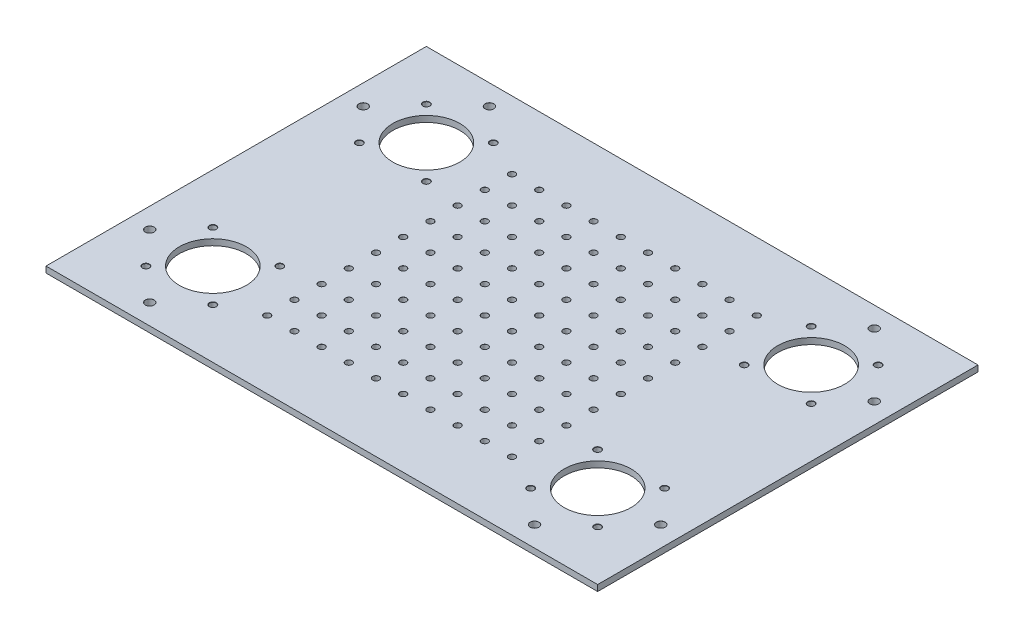
SolidWorks part; units mm, degrees
ref_plane "Front Plane" through (0, 0, 0) normal (0, 0, 1) x (1, 0, 0)
ref_plane "Top Plane" through (0, 0, 0) normal (0, 1, 0) x (1, 0, 0)
ref_plane "Right Plane" through (0, 0, 0) normal (1, 0, 0) x (0, 0, -1)
sketch "Sketch1" plane through (0, 0, 0) normal (0, 1, 0) x (1, 0, 0)
  line L0 (-115.9, 93.7) -> (-115.9, -93.7) construction
  line L1 (-135.9, -93.7) -> (135.9, -93.7)
  line L2 (-135.9, -93.7) -> (-135.9, 93.7)
  line L3 (-135.9, 93.7) -> (135.9, 93.7)
  line L4 (135.9, -93.7) -> (135.9, 93.7)
  line L5 (-135.9, -93.7) -> (135.9, 93.7) construction
  line L6 (-135.9, 93.7) -> (135.9, -93.7) construction
  line L7 (-94.8, -52.6) -> (94.8, -52.6) construction
  line L8 (-94.8, -52.6) -> (-94.8, 52.6) construction
  line L9 (-94.8, 52.6) -> (94.8, 52.6) construction
  line L10 (94.8, -52.6) -> (94.8, 52.6) construction
  line L11 (-94.8, -52.6) -> (94.8, 52.6) construction
  line L12 (-94.8, 52.6) -> (94.8, -52.6) construction
  line L13 (-115.9, 73.7) -> (-73.7, 73.7) construction
  line L14 (-115.9, 73.7) -> (-115.9, 31.5) construction
  line L15 (-115.9, 31.5) -> (-73.7, 31.5) construction
  line L16 (-73.7, 73.7) -> (-73.7, 31.5) construction
  line L17 (-115.9, 73.7) -> (-73.7, 31.5) construction
  line L18 (-115.9, 31.5) -> (-73.7, 73.7) construction
  line L19 (-115.9, 73.7) -> (135.9, 73.7) construction
  line L20 (-135.9, 73.7) -> (-115.9, 73.7) construction
  line L21 (-94.8, 73.7) -> (-94.8, 93.7) construction
  line L22 (-115.9, 52.6) -> (-135.9, 52.6) construction
  line L23 (-60.3, 93.7) -> (-60.3, -93.7) construction
  line L24 (-115.9, -73.7) -> (-73.7, -73.7) construction
  line L25 (-115.9, -73.7) -> (-115.9, -31.5) construction
  line L26 (-115.9, -31.5) -> (-73.7, -31.5) construction
  line L27 (-73.7, -73.7) -> (-73.7, -31.5) construction
  line L28 (-115.9, -73.7) -> (-73.7, -31.5) construction
  line L29 (-115.9, -31.5) -> (-73.7, -73.7) construction
  line L30 (73.7, 73.7) -> (115.9, 73.7) construction
  line L31 (73.7, 73.7) -> (73.7, 31.5) construction
  line L32 (73.7, 31.5) -> (115.9, 31.5) construction
  line L33 (115.9, 73.7) -> (115.9, 31.5) construction
  line L34 (73.7, 73.7) -> (115.9, 31.5) construction
  line L35 (73.7, 31.5) -> (115.9, 73.7) construction
  line L36 (73.7, -31.5) -> (115.9, -31.5) construction
  line L37 (73.7, -31.5) -> (73.7, -73.7) construction
  line L38 (73.7, -73.7) -> (115.9, -73.7) construction
  line L39 (115.9, -31.5) -> (115.9, -73.7) construction
  line L40 (73.7, -31.5) -> (115.9, -73.7) construction
  line L41 (73.7, -73.7) -> (115.9, -31.5) construction
  line L42 (-60.3, 60.3) -> (-60.3, 46.9) construction
  line L43 (-60.3, 60.3) -> (-46.9, 60.3) construction
  circle A0 centre (-94.8, 52.6) radius 16.5
  circle A1 centre (-94.8, -52.6) radius 16.5
  circle A2 centre (94.8, -52.6) radius 16.5
  circle A3 centre (94.8, 52.6) radius 16.5
  circle A4 centre (-60.3, 60.3) radius 1.6 construction
  point P0 (0, 0)
  point P6 (0, 0)
  point P37 (-60.3, 46.9)
  point P39 (-60.3, 60.3)
  point P40 (-60.3, 33.5)
  point P41 (-60.3, 20.1)
  point P42 (-60.3, 6.7)
  point P43 (-60.3, -6.7)
  point P44 (-60.3, -20.1)
  point P45 (-60.3, -33.5)
  point P46 (-60.3, -46.9)
  point P47 (-60.3, -60.3)
  point P53 (-46.9, 60.3)
  point P54 (-46.9, 46.9)
  point P55 (-46.9, 33.5)
  point P56 (-46.9, 20.1)
  point P57 (-46.9, 6.7)
  point P58 (-46.9, -6.7)
  point P59 (-46.9, -20.1)
  point P60 (-46.9, -33.5)
  point P61 (-46.9, -46.9)
  point P62 (-46.9, -60.3)
  point P63 (-33.5, 60.3)
  point P64 (-33.5, 46.9)
  point P65 (-33.5, 33.5)
  point P66 (-33.5, 20.1)
  point P67 (-33.5, 6.7)
  point P68 (-33.5, -6.7)
  point P69 (-33.5, -20.1)
  point P70 (-33.5, -33.5)
  point P71 (-33.5, -46.9)
  point P72 (-33.5, -60.3)
  point P73 (-20.1, 60.3)
  point P74 (-20.1, 46.9)
  point P75 (-20.1, 33.5)
  point P76 (-20.1, 20.1)
  point P77 (-20.1, 6.7)
  point P78 (-20.1, -6.7)
  point P79 (-20.1, -20.1)
  point P80 (-20.1, -33.5)
  point P81 (-20.1, -46.9)
  point P82 (-20.1, -60.3)
  point P83 (-6.7, 60.3)
  point P84 (-6.7, 46.9)
  point P85 (-6.7, 33.5)
  point P86 (-6.7, 20.1)
  point P87 (-6.7, 6.7)
  point P88 (-6.7, -6.7)
  point P89 (-6.7, -20.1)
  point P90 (-6.7, -33.5)
  point P91 (-6.7, -46.9)
  point P92 (-6.7, -60.3)
  point P93 (6.7, 60.3)
  point P94 (6.7, 46.9)
  point P95 (6.7, 33.5)
  point P96 (6.7, 20.1)
  point P97 (6.7, 6.7)
  point P98 (6.7, -6.7)
  point P99 (6.7, -20.1)
  point P100 (6.7, -33.5)
  point P101 (6.7, -46.9)
  point P102 (6.7, -60.3)
  point P103 (20.1, 60.3)
  point P104 (20.1, 46.9)
  point P105 (20.1, 33.5)
  point P106 (20.1, 20.1)
  point P107 (20.1, 6.7)
  point P108 (20.1, -6.7)
  point P109 (20.1, -20.1)
  point P110 (20.1, -33.5)
  point P111 (20.1, -46.9)
  point P112 (20.1, -60.3)
  point P113 (33.5, 60.3)
  point P114 (33.5, 46.9)
  point P115 (33.5, 33.5)
  point P116 (33.5, 20.1)
  point P117 (33.5, 6.7)
  point P118 (33.5, -6.7)
  point P119 (33.5, -20.1)
  point P120 (33.5, -33.5)
  point P121 (33.5, -46.9)
  point P122 (33.5, -60.3)
  point P123 (46.9, 60.3)
  point P124 (46.9, 46.9)
  point P125 (46.9, 33.5)
  point P126 (46.9, 20.1)
  point P127 (46.9, 6.7)
  point P128 (46.9, -6.7)
  point P129 (46.9, -20.1)
  point P130 (46.9, -33.5)
  point P131 (46.9, -46.9)
  point P132 (46.9, -60.3)
  point P133 (60.3, 60.3)
  point P134 (60.3, 46.9)
  point P135 (60.3, 33.5)
  point P136 (60.3, 20.1)
  point P137 (60.3, 6.7)
  point P138 (60.3, -6.7)
  point P139 (60.3, -20.1)
  point P140 (60.3, -33.5)
  point P141 (60.3, -46.9)
  point P142 (60.3, -60.3)
  dimension "D11" = 33
  dimension "D12" = 3.2
  dimension "D1" = 42.2
  dimension "D2" = 20
  dimension "D3" = 13.4
  dimension "D6" = 13.4
  dimension "D7" = 13.4
  dimension "D8" = 13.4
  dimension "D9" = 13.4
  dimension "D10" = 13.4
  dimension "PlungerplateWidth" = 271.8
  dimension "PlungerplateHeight" = 187.4
  dimension "D4" = 10
  dimension "D5" = 10
extrude "Boss-Extrude1" add sketch "Sketch1" along normal blind 3
hole_wizard "M3 Clearance Hole1" positions "Sketch11" profile "Sketch13" hole size "M3" standard "DIN" end condition through all
sketch "Sketch11" plane through (0, 3, 0) normal (0, 1, 0) x (1, 0, 0)
  line L1 (-111.3, 69.1) -> (-78.3, 69.1)
  line L2 (-111.3, 69.1) -> (-111.3, 36.1)
  line L3 (-111.3, 36.1) -> (-78.3, 36.1)
  line L4 (-78.3, 69.1) -> (-78.3, 36.1)
  line L5 (-111.3, 69.1) -> (-78.3, 36.1) construction
  line L6 (-111.3, 36.1) -> (-78.3, 69.1) construction
  line L7 (0, 0) -> (0, 50000) construction
  line L8 (0, 0) -> (50000, 0) construction
  line L9 (-111.3, -36.1) -> (-78.3, -69.1) construction
  line L10 (-111.3, -69.1) -> (-78.3, -36.1) construction
  line L11 (-78.3, -69.1) -> (-78.3, -36.1)
  line L12 (-111.3, -36.1) -> (-78.3, -36.1)
  line L13 (-111.3, -69.1) -> (-111.3, -36.1)
  line L14 (-111.3, -69.1) -> (-78.3, -69.1)
  line L15 (111.3, -69.1) -> (78.3, -36.1) construction
  line L16 (111.3, -36.1) -> (78.3, -69.1) construction
  line L17 (111.3, 36.1) -> (78.3, 69.1) construction
  line L18 (111.3, 69.1) -> (78.3, 36.1) construction
  line L19 (111.3, -69.1) -> (78.3, -69.1)
  line L20 (111.3, -69.1) -> (111.3, -36.1)
  line L21 (111.3, -36.1) -> (78.3, -36.1)
  line L22 (78.3, -69.1) -> (78.3, -36.1)
  line L23 (78.3, 69.1) -> (78.3, 36.1)
  line L24 (111.3, 36.1) -> (78.3, 36.1)
  line L25 (111.3, 69.1) -> (111.3, 36.1)
  line L26 (111.3, 69.1) -> (78.3, 69.1)
  point P2 (-78.3, 36.1)
  point P207 (-111.3, 69.1)
  point P208 (-111.3, 36.1)
  point P209 (-78.3, 69.1)
  point P223 (-94.8, 52.6)
  point P235 (-78.3, -69.1)
  point P236 (-111.3, -36.1)
  point P237 (-111.3, -69.1)
  point P238 (-78.3, -36.1)
  point P247 (78.3, -36.1)
  point P248 (111.3, -69.1)
  point P249 (111.3, -36.1)
  point P250 (78.3, -69.1)
  point P251 (78.3, 69.1)
  point P252 (111.3, 36.1)
  point P253 (111.3, 69.1)
  point P254 (78.3, 36.1)
  dimension "D1" = 33
sketch "Sketch13" plane through (-78.3, 3, -36.1) normal (1, 0, 0) x (0, 0, 1)
  line L0 (0, 0) -> (0, 3)
  line L1 (0, 3) -> (1.6, 3)
  line L2 (1.6, 3) -> (1.6, 0.125)
  line L3 (1.6, 0.125) -> (1.725, 0)
  line L5 (1.725, 0) -> (0, 0)
  line L6 (-1.6, 0.125) -> (-1.725, 0) construction
  line L11 (0, -6.35) -> (0, 107.95) construction
  dimension "Thru Hole Dia." = 3.2
  dimension "Thru Hole Depth" = 3
  dimension "Near C'Sink Dia." = 3.45
  dimension "Near C'Sink Angle" = 90
hole_wizard "M4 Clearance Hole2" positions "Sketch14" profile "Sketch15" hole size "M4" standard "DIN" end condition through all
sketch "Sketch14" plane through (0, 3, 0) normal (0, 1, 0) x (1, 0, 0)
  line L0 (-135.9, -93.7) -> (-135.9, 93.7) construction
  line L1 (-135.9, 93.7) -> (135.9, 93.7) construction
  line L2 (-94.8, 52.6) -> (94.8, 52.6) construction
  line L3 (-94.8, -52.6) -> (-94.8, 52.6) construction
  line L4 (0, 0) -> (50000, 0) construction
  line L5 (-135.9, -93.7) -> (135.9, 93.7) construction
  line L6 (0, 0) -> (0, -50000) construction
  point P0 (-94.8, 83.7)
  point P1 (-125.9, 52.6)
  point P17 (0, 0)
  point P21 (-125.9, -52.6)
  point P22 (-94.8, -83.7)
  point P23 (94.8, -83.7)
  point P24 (125.9, -52.6)
  point P25 (125.9, 52.6)
  point P26 (94.8, 83.7)
  dimension "D1" = 10
  dimension "D2" = 10
sketch "Sketch15" plane through (-94.8, 3, -83.7) normal (1, 0, 0) x (0, 0, 1)
  line L0 (0, 0) -> (0, 3)
  line L1 (0, 3) -> (2.15, 3)
  line L2 (2.15, 3) -> (2.15, 0.025)
  line L3 (2.15, 0.025) -> (2.175, 0)
  line L5 (2.175, 0) -> (0, 0)
  line L6 (-2.15, 0.025) -> (-2.175, 0) construction
  line L11 (0, -6.35) -> (0, 107.95) construction
  dimension "Thru Hole Dia." = 4.3
  dimension "Thru Hole Depth" = 3
  dimension "Near C'Sink Dia." = 4.35
  dimension "Near C'Sink Angle" = 90
hole_wizard "Ø3.2 (3.2) Diameter Hole1" positions "Sketch16" profile "Sketch17" hole size "Ø3.2" standard "DIN" end condition through all
sketch "Sketch16" plane through (0, 3, 0) normal (0, 1, 0) x (1, 0, 0)
  point P0 (-60.3, 60.3)
  point P9 (-46.9, 60.3)
  point P10 (-33.5, 60.3)
  point P11 (-20.1, 60.3)
  point P12 (-6.7, 60.3)
  point P13 (6.7, 60.3)
  point P14 (20.1, 60.3)
  point P15 (33.5, 60.3)
  point P16 (46.9, 60.3)
  point P17 (60.3, 60.3)
  point P18 (-46.9, 46.9)
  point P19 (-33.5, 46.9)
  point P20 (-20.1, 46.9)
  point P21 (-6.7, 46.9)
  point P22 (6.7, 46.9)
  point P23 (20.1, 46.9)
  point P24 (33.5, 46.9)
  point P25 (46.9, 46.9)
  point P26 (60.3, 46.9)
  point P27 (-46.9, 33.5)
  point P28 (-33.5, 33.5)
  point P29 (-20.1, 33.5)
  point P30 (-6.7, 33.5)
  point P31 (6.7, 33.5)
  point P32 (20.1, 33.5)
  point P33 (33.5, 33.5)
  point P34 (46.9, 33.5)
  point P35 (60.3, 33.5)
  point P36 (-46.9, 20.1)
  point P37 (-33.5, 20.1)
  point P38 (-20.1, 20.1)
  point P39 (-6.7, 20.1)
  point P40 (6.7, 20.1)
  point P41 (20.1, 20.1)
  point P42 (33.5, 20.1)
  point P43 (46.9, 20.1)
  point P44 (60.3, 20.1)
  point P45 (-46.9, 6.7)
  point P46 (-33.5, 6.7)
  point P47 (-20.1, 6.7)
  point P48 (-6.7, 6.7)
  point P49 (6.7, 6.7)
  point P50 (20.1, 6.7)
  point P51 (33.5, 6.7)
  point P52 (46.9, 6.7)
  point P53 (60.3, 6.7)
  point P54 (-46.9, -6.7)
  point P55 (-33.5, -6.7)
  point P56 (-20.1, -6.7)
  point P57 (-6.7, -6.7)
  point P58 (6.7, -6.7)
  point P59 (20.1, -6.7)
  point P60 (33.5, -6.7)
  point P61 (46.9, -6.7)
  point P62 (60.3, -6.7)
  point P63 (-46.9, -20.1)
  point P64 (-33.5, -20.1)
  point P65 (-20.1, -20.1)
  point P66 (-6.7, -20.1)
  point P67 (6.7, -20.1)
  point P68 (20.1, -20.1)
  point P69 (33.5, -20.1)
  point P70 (46.9, -20.1)
  point P71 (60.3, -20.1)
  point P72 (-46.9, -33.5)
  point P73 (-33.5, -33.5)
  point P74 (-20.1, -33.5)
  point P75 (-6.7, -33.5)
  point P76 (6.7, -33.5)
  point P77 (20.1, -33.5)
  point P78 (33.5, -33.5)
  point P79 (46.9, -33.5)
  point P80 (60.3, -33.5)
  point P81 (-46.9, -46.9)
  point P82 (-33.5, -46.9)
  point P83 (-20.1, -46.9)
  point P84 (-6.7, -46.9)
  point P85 (6.7, -46.9)
  point P86 (20.1, -46.9)
  point P87 (33.5, -46.9)
  point P88 (46.9, -46.9)
  point P89 (60.3, -46.9)
  point P90 (-46.9, -60.3)
  point P91 (-33.5, -60.3)
  point P92 (-20.1, -60.3)
  point P93 (-6.7, -60.3)
  point P94 (6.7, -60.3)
  point P95 (20.1, -60.3)
  point P96 (33.5, -60.3)
  point P97 (46.9, -60.3)
  point P98 (60.3, -60.3)
  point P99 (-60.3, 46.9)
  point P100 (-60.3, 33.5)
  point P101 (-60.3, 20.1)
  point P102 (-60.3, 6.7)
  point P103 (-60.3, -6.7)
  point P104 (-60.3, -20.1)
  point P105 (-60.3, -33.5)
  point P106 (-60.3, -46.9)
  point P107 (-60.3, -60.3)
  dimension "D1" = 10
  dimension "D2" = 10
sketch "Sketch17" plane through (-60.3, 3, -60.3) normal (1, 0, 0) x (0, 0, 1)
  line L0 (0, 0) -> (0, 3)
  line L1 (0, 3) -> (1.6, 3)
  line L2 (1.6, 3) -> (1.6, 0.025)
  line L3 (1.6, 0.025) -> (1.625, 0)
  line L5 (1.625, 0) -> (0, 0)
  line L6 (-1.6, 0.025) -> (-1.625, 0) construction
  line L11 (0, -6.35) -> (0, 107.95) construction
  dimension "Thru Hole Dia." = 3.2
  dimension "Thru Hole Depth" = 3
  dimension "Near C'Sink Dia." = 3.25
  dimension "Near C'Sink Angle" = 90
equation "\"D7@Sketch1\"=\"D6@Sketch1\""
equation "\"D10@Sketch1\"=\"D9@Sketch1\""
equation "\"D3@Sketch1\"=\"D9@Sketch1\""
